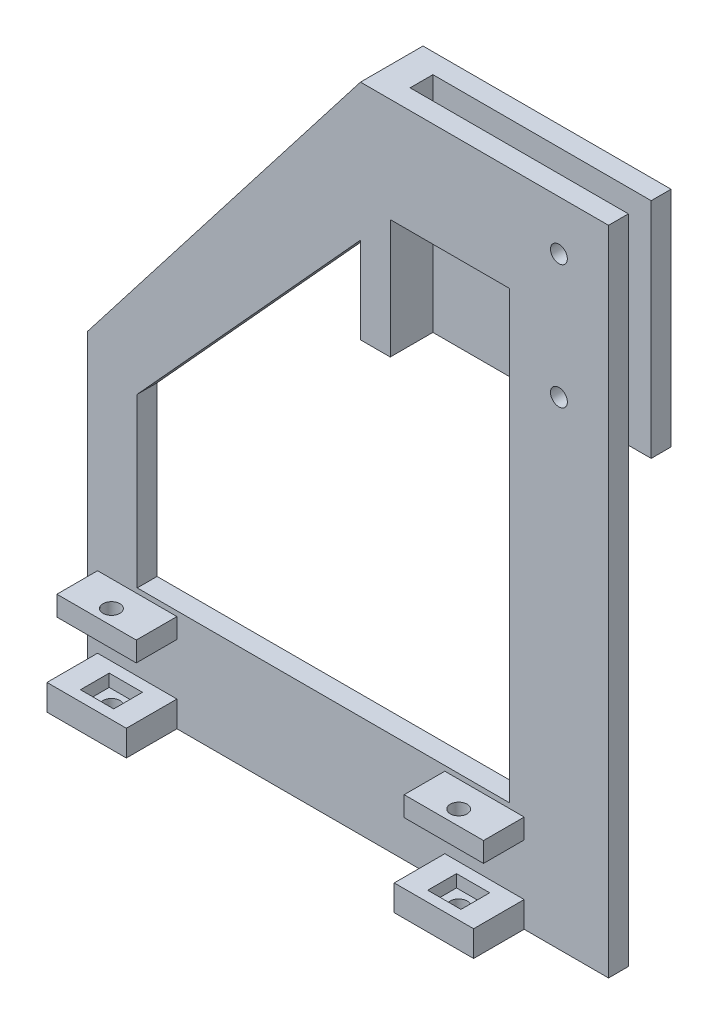
SolidWorks part; units mm, degrees
ref_plane "前视基准面" through (0, 0, 0) normal (0, 0, 1) x (1, 0, 0)
ref_plane "上视基准面" through (0, 0, 0) normal (0, 1, 0) x (1, 0, 0)
ref_plane "右视基准面" through (0, 0, 0) normal (1, 0, 0) x (0, 0, -1)
other "Configuration Table"
sketch "草图1" plane through (0, 0, 0) normal (0, 0, 1) x (1, 0, 0)
  line L0 (-65, -5.4) -> (40, -5.4)
  line L1 (40, -5.4) -> (40, 126)
  line L2 (40, 126) -> (-10, 126)
  line L3 (-10, 126) -> (-65, 55)
  line L4 (-65, 55) -> (-65, -5.4)
  dimension "D1" = 40
  dimension "D2" = 10
  dimension "D3" = 65
  dimension "D4" = 55
  dimension "D5" = 126
  dimension "D6" = 5.4
extrude "卡座外侧承力框" add sketch "草图1" along normal blind 4 from offset 4.2
sketch "草图2" plane through (0, 0, 0) normal (0, 0, 1) x (1, 0, 0)
  line L0 (-55, 15.2) -> (20, 15.2)
  line L1 (20, 15.2) -> (20, 105)
  line L2 (20, 105) -> (-4, 105)
  line L3 (-4, 105) -> (-55, 49)
  line L4 (-55, 49) -> (-55, 15.2)
  dimension "D1" = 20
  dimension "D2" = 4
  dimension "D3" = 55
  dimension "D4" = 15.2
  dimension "D5" = 49
  dimension "D6" = 105
extrude "承力框减重窗口" cut sketch "草图2" against normal through all and the other way through all
sketch "草图3" plane through (0, 0, 0) normal (0, 0, 1) x (1, 0, 0)
  line L1 (-63, 10.2) -> (-47, 10.2)
  line L2 (-63, 10.2) -> (-63, 14.2)
  line L3 (-63, 14.2) -> (-47, 14.2)
  line L4 (-47, 10.2) -> (-47, 14.2)
  line L6 (7, 10.2) -> (23, 10.2)
  line L7 (7, 10.2) -> (7, 14.2)
  line L8 (7, 14.2) -> (23, 14.2)
  line L9 (23, 10.2) -> (23, 14.2)
  dimension "D1" = 7
  dimension "D2" = 23
  dimension "D3" = 47
  dimension "D4" = 10.2
  dimension "D5" = 14.2
extrude "上卡唇" add sketch "草图3" along normal blind 12.2 from offset 4.2
sketch "草图4" plane through (0, 0, 0) normal (0, 0, 1) x (1, 0, 0)
  line L1 (-63, -5.4) -> (-47, -5.4)
  line L2 (-63, -5.4) -> (-63, -2.7)
  line L3 (-63, -2.7) -> (-47, -2.7)
  line L4 (-47, -5.4) -> (-47, -2.7)
  line L6 (7, -5.4) -> (23, -5.4)
  line L7 (7, -5.4) -> (7, -2.7)
  line L8 (7, -2.7) -> (23, -2.7)
  line L9 (23, -5.4) -> (23, -2.7)
  dimension "D1" = 7
  dimension "D2" = 23
  dimension "D3" = 47
  dimension "D4" = 2.7
  dimension "D5" = 5.4
extrude "下卡唇螺母承力底" add sketch "草图4" along normal blind 14.2 from offset 4.2
sketch "草图5" plane through (0, 0, 0) normal (0, 1, 0) x (1, 0, 0)
  line L1 (-63, -10) -> (-47, -10)
  line L2 (-63, -10) -> (-63, 4.2)
  line L3 (-63, 4.2) -> (-47, 4.2)
  line L4 (-47, -10) -> (-47, 4.2)
  line L6 (-58.35, -7.9) -> (-51.65, -7.9)
  line L7 (-58.35, -7.9) -> (-58.35, -2.1)
  line L8 (-58.35, -2.1) -> (-51.65, -2.1)
  line L9 (-51.65, -7.9) -> (-51.65, -2.1)
  line L11 (7, -10) -> (23, -10)
  line L12 (7, -10) -> (7, 4.2)
  line L13 (7, 4.2) -> (23, 4.2)
  line L14 (23, -10) -> (23, 4.2)
  line L16 (11.65, -7.9) -> (18.35, -7.9)
  line L17 (11.65, -7.9) -> (11.65, -2.1)
  line L18 (11.65, -2.1) -> (18.35, -2.1)
  line L19 (18.35, -7.9) -> (18.35, -2.1)
  dimension "D1" = 7
  dimension "D2" = 11.65
  dimension "D3" = 18.35
  dimension "D4" = 23
  dimension "D5" = 47
  dimension "D6" = 51.65
  dimension "D7" = 4.2
  dimension "D8" = 2.1
  dimension "D9" = 7.9
  dimension "D10" = 10
extrude "下卡唇M3螺母防转槽" add sketch "草图5" along normal blind 2.5 from offset 2.7
sketch "草图6" plane through (0, 0, 0) normal (0, 0, 1) x (1, 0, 0)
  line L1 (-10, 81) -> (-4, 81)
  line L2 (-10, 81) -> (-10, 126)
  line L3 (-10, 126) -> (-4, 126)
  line L4 (-4, 81) -> (-4, 126)
  dimension "D1" = 4
  dimension "D2" = 10
  dimension "D3" = 81
  dimension "D4" = 126
extrude "梁根后挡" add sketch "草图6" along normal blind 12.6 from offset 12.8
sketch "草图7" plane through (0, 0, 0) normal (0, 0, 1) x (1, 0, 0)
  line L1 (-10, 81) -> (40, 81)
  line L2 (-10, 81) -> (-10, 126)
  line L3 (-10, 126) -> (40, 126)
  line L4 (40, 81) -> (40, 126)
  dimension "D1" = 40
  dimension "D2" = 10
  dimension "D3" = 81
  dimension "D4" = 126
extrude "梁根外夹片" add sketch "草图7" along normal blind 4 from offset 12.8
sketch "草图8" plane through (0, 0, 0) normal (0, 0, 1) x (1, 0, 0)
  circle A0 centre (30, 91) radius 1.7
  circle A1 centre (30, 116) radius 1.7
  dimension "D1" = 3.4
  dimension "D2" = 30
  dimension "D3" = 91
  dimension "D4" = 116
extrude "梁根两孔3p4" cut sketch "草图8" against normal through all and the other way through all
sketch "草图9" plane through (0, 0, 0) normal (0, 1, 0) x (1, 0, 0)
  circle A0 centre (-55, -5) radius 1.7
  circle A1 centre (15, -5) radius 1.7
  dimension "D1" = 3.4
  dimension "D2" = 15
  dimension "D3" = 55
  dimension "D4" = 5
extrude "板边压紧孔3p4" cut sketch "草图9" against normal through all and the other way through all
